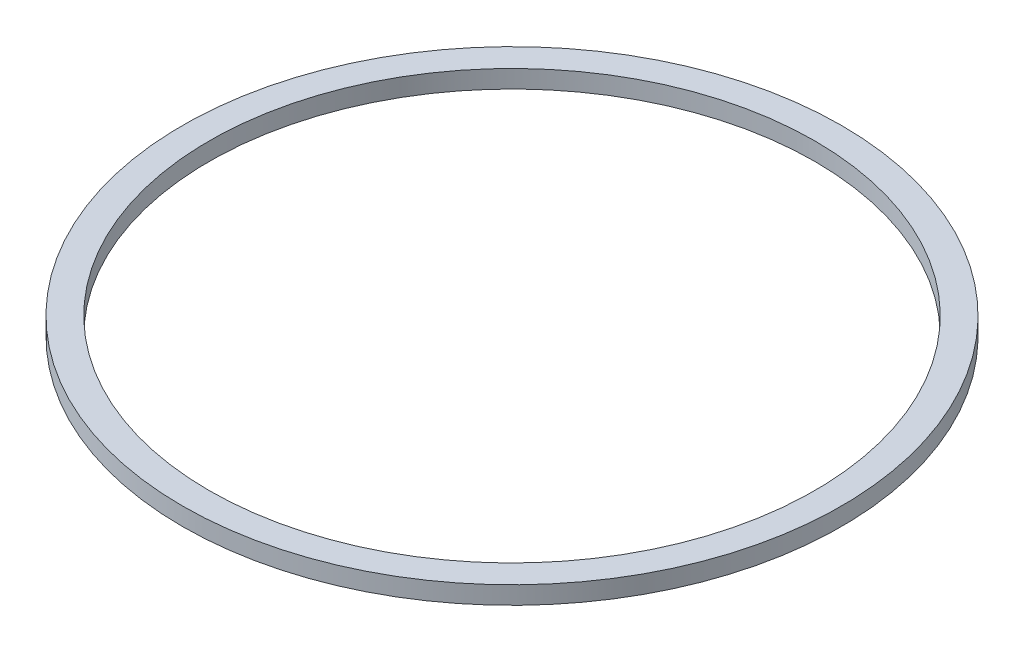
SolidWorks part; units mm, degrees
ref_plane "前视基准面" through (0, 0, 0) normal (0, 0, 1) x (1, 0, 0)
ref_plane "上视基准面" through (0, 0, 0) normal (0, 1, 0) x (1, 0, 0)
ref_plane "右视基准面" through (0, 0, 0) normal (1, 0, 0) x (0, 0, -1)
sketch "草图1" plane through (0, 0, 0) normal (0, 1, 0) x (1, 0, 0)
  circle A0 centre (0, 0) radius 185
  circle A1 centre (0, 0) radius 170
  dimension "D1" = 370
  dimension "D2" = 340
extrude "凸台-拉伸1" add sketch "草图1" along normal blind 10
